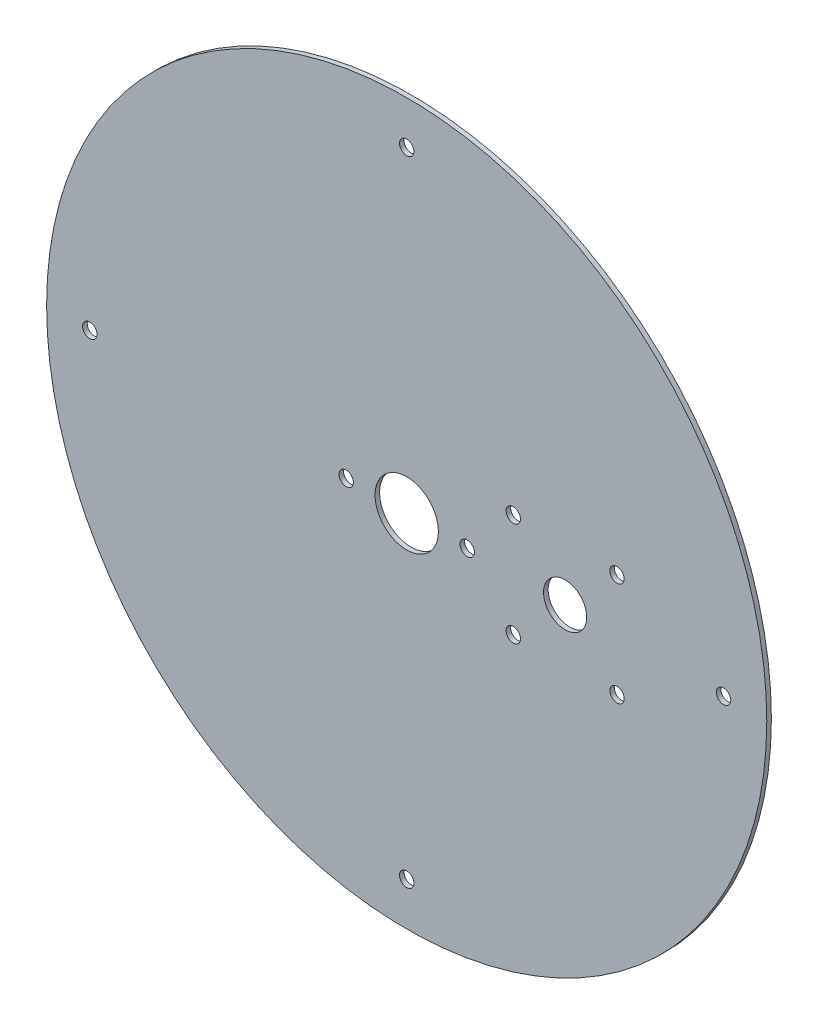
SolidWorks part; units mm, degrees
ref_plane "正面" through (0, 0, 0) normal (0, 0, 1) x (1, 0, 0)
ref_plane "平面" through (0, 0, 0) normal (0, 1, 0) x (1, 0, 0)
ref_plane "右側面" through (0, 0, 0) normal (1, 0, 0) x (0, 0, -1)
sketch "ｽｹｯﾁ1" plane through (0, 0, 0) normal (0, 0, 1) x (1, 0, 0)
  circle A0 centre (0, 0) radius 125
  dimension "D1" = 250
extrude "ﾎﾞｽ - 押し出し1" add sketch "ｽｹｯﾁ1" along normal blind 1.6
sketch "ｽｹｯﾁ2" plane through (0, 0, 1.6) normal (0, 0, 1) x (1, 0, 0)
  circle A0 centre (0, 0) radius 11
  dimension "D1" = 22
extrude "ｶｯﾄ - 押し出し1" cut sketch "ｽｹｯﾁ2" against normal through all
sketch "ｽｹｯﾁ3" plane through (0, 0, 1.6) normal (0, 0, 1) x (1, 0, 0)
  line L0 (0, 0) -> (-125, 0) construction
  line L3 (0, 0) -> (55, 0) construction
  line L4 (0, 0) -> (55, 0) construction
  circle A0 centre (0, 0) radius 125 construction
  circle A1 centre (55, 0) radius 7.5
  dimension "D1" = 15
  dimension "D2" = 55
extrude "ｶｯﾄ - 押し出し2" cut sketch "ｽｹｯﾁ3" against normal through all
sketch "ｽｹｯﾁ4" plane through (0, 0, 1.6) normal (0, 0, 1) x (1, 0, 0)
  line L0 (0, 0) -> (110, 0) construction
  line L1 (0, 0) -> (-21, 0) construction
  line L2 (0, 0) -> (21, 0) construction
  line L3 (0, 125) -> (0, 0) construction
  line L4 (0, 0) -> (0, -125) construction
  line L5 (0, 0) -> (0, -110) construction
  line L6 (0, 0) -> (0, 110) construction
  circle A1 centre (0, 0) radius 125 construction
  dimension "D1" = 110
  dimension "D2" = 21
  dimension "D3" = 125
  dimension "D4" = 21
  dimension "D5" = 110
  dimension "D6" = 110
hole_wizard "M6x1.0 ねじ穴1" positions "3Dｽｹｯﾁ1" profile "ｽｹｯﾁ5" tap size "M6x1.0" standard "JIS" end condition through all
sketch3d "3Dｽｹｯﾁ1"
  point P0 (110, 0, 1.6)
sketch "ｽｹｯﾁ5" plane through (110, 0, 1.6) normal (1, 0, 0) x (0, -1, 0)
  line L0 (0, 0) -> (0, 1.6)
  line L1 (0, 1.6) -> (2.5, 1.6)
  line L2 (2.5, 1.6) -> (2.5, 0)
  line L5 (2.5, 0) -> (0, 0)
  line L11 (0, -6.35) -> (0, 107.95) construction
  dimension "ねじ山の主要直径" = 5
  dimension "次ｻｰﾌｪｽまでのねじ下穴ﾄﾞﾘﾙの深さ" = 1.6
sketch "ｽｹｯﾁ6" plane through (0, 0, 1.6) normal (0, 0, 1) x (1, 0, 0)
  line L0 (0, 0) -> (-110, 0) construction
  dimension "D1" = 110
hole_wizard "M6x1.0 ねじ穴2" positions "3Dｽｹｯﾁ2" profile "ｽｹｯﾁ7" tap size "M6x1.0" standard "JIS" end condition through all
sketch3d "3Dｽｹｯﾁ2"
  point P0 (-110, 0, 1.6)
sketch "ｽｹｯﾁ7" plane through (-110, 0, 1.6) normal (1, 0, 0) x (0, -1, 0)
  line L0 (0, 0) -> (0, 1.6)
  line L1 (0, 1.6) -> (2.5, 1.6)
  line L2 (2.5, 1.6) -> (2.5, 0)
  line L5 (2.5, 0) -> (0, 0)
  line L11 (0, -6.35) -> (0, 107.95) construction
  dimension "ねじ山の主要直径" = 5
  dimension "次ｻｰﾌｪｽまでのねじ下穴ﾄﾞﾘﾙの深さ" = 1.6
hole_wizard "M6x1.0 ねじ穴3" positions "3Dｽｹｯﾁ3" profile "ｽｹｯﾁ8" tap size "M6x1.0" standard "JIS" end condition through all
sketch3d "3Dｽｹｯﾁ3"
  point P0 (-21, 0, 1.6)
sketch "ｽｹｯﾁ8" plane through (-21, 0, 1.6) normal (1, 0, 0) x (0, -1, 0)
  line L0 (0, 0) -> (0, 1.6)
  line L1 (0, 1.6) -> (2.5, 1.6)
  line L2 (2.5, 1.6) -> (2.5, 0)
  line L5 (2.5, 0) -> (0, 0)
  line L11 (0, -6.35) -> (0, 107.95) construction
  dimension "ねじ山の主要直径" = 5
  dimension "次ｻｰﾌｪｽまでのねじ下穴ﾄﾞﾘﾙの深さ" = 1.6
hole_wizard "M6x1.0 ねじ穴4" positions "3Dｽｹｯﾁ4" profile "ｽｹｯﾁ9" tap size "M6x1.0" standard "JIS" end condition through all
sketch3d "3Dｽｹｯﾁ4"
  point P0 (21, 0, 1.6)
sketch "ｽｹｯﾁ9" plane through (21, 0, 1.6) normal (1, 0, 0) x (0, -1, 0)
  line L0 (0, 0) -> (0, 1.6)
  line L1 (0, 1.6) -> (2.5, 1.6)
  line L2 (2.5, 1.6) -> (2.5, 0)
  line L5 (2.5, 0) -> (0, 0)
  line L11 (0, -6.35) -> (0, 107.95) construction
  dimension "ねじ山の主要直径" = 5
  dimension "次ｻｰﾌｪｽまでのねじ下穴ﾄﾞﾘﾙの深さ" = 1.6
sketch "ｽｹｯﾁ10" plane through (0, 0, 1.6) normal (0, 0, 1) x (1, 0, 0)
  line L0 (55, 0) -> (55, 18) construction
  line L1 (55, 18) -> (37, 18) construction
  line L2 (37, 18) -> (37, -18) construction
  line L3 (37, -18) -> (73, -18) construction
  line L4 (73, -18) -> (73, 18) construction
  dimension "D1" = 18
  dimension "D2" = 18
  dimension "D3" = 36
  dimension "D4" = 36
  dimension "D5" = 36
hole_wizard "M6x1.0 ねじ穴5" positions "3Dｽｹｯﾁ5" profile "ｽｹｯﾁ11" tap size "M6x1.0" standard "JIS" end condition through all
sketch3d "3Dｽｹｯﾁ5"
  point P0 (37, 18, 1.6)
  point P3 (73, 18, 1.6)
  point P6 (73, -18, 1.6)
  point P9 (37, -18, 1.6)
sketch "ｽｹｯﾁ11" plane through (37, 18, 1.6) normal (1, 0, 0) x (0, -1, 0)
  line L0 (0, 0) -> (0, 1.6)
  line L1 (0, 1.6) -> (2.5, 1.6)
  line L2 (2.5, 1.6) -> (2.5, 0)
  line L5 (2.5, 0) -> (0, 0)
  line L11 (0, -6.35) -> (0, 107.95) construction
  dimension "ねじ山の主要直径" = 5
  dimension "次ｻｰﾌｪｽまでのねじ下穴ﾄﾞﾘﾙの深さ" = 1.6
hole_wizard "M6x1.0 ねじ穴6" positions "3Dｽｹｯﾁ6" profile "ｽｹｯﾁ12" tap size "M6x1.0" standard "JIS" end condition through all
sketch3d "3Dｽｹｯﾁ6"
  point P0 (0, 110, 1.6)
  point P3 (0, -110, 1.6)
sketch "ｽｹｯﾁ12" plane through (0, 110, 1.6) normal (1, 0, 0) x (0, -1, 0)
  line L0 (0, 0) -> (0, 1.6)
  line L1 (0, 1.6) -> (2.5, 1.6)
  line L2 (2.5, 1.6) -> (2.5, 0)
  line L5 (2.5, 0) -> (0, 0)
  line L11 (0, -6.35) -> (0, 107.95) construction
  dimension "ねじ山の主要直径" = 5
  dimension "次ｻｰﾌｪｽまでのねじ下穴ﾄﾞﾘﾙの深さ" = 1.6
